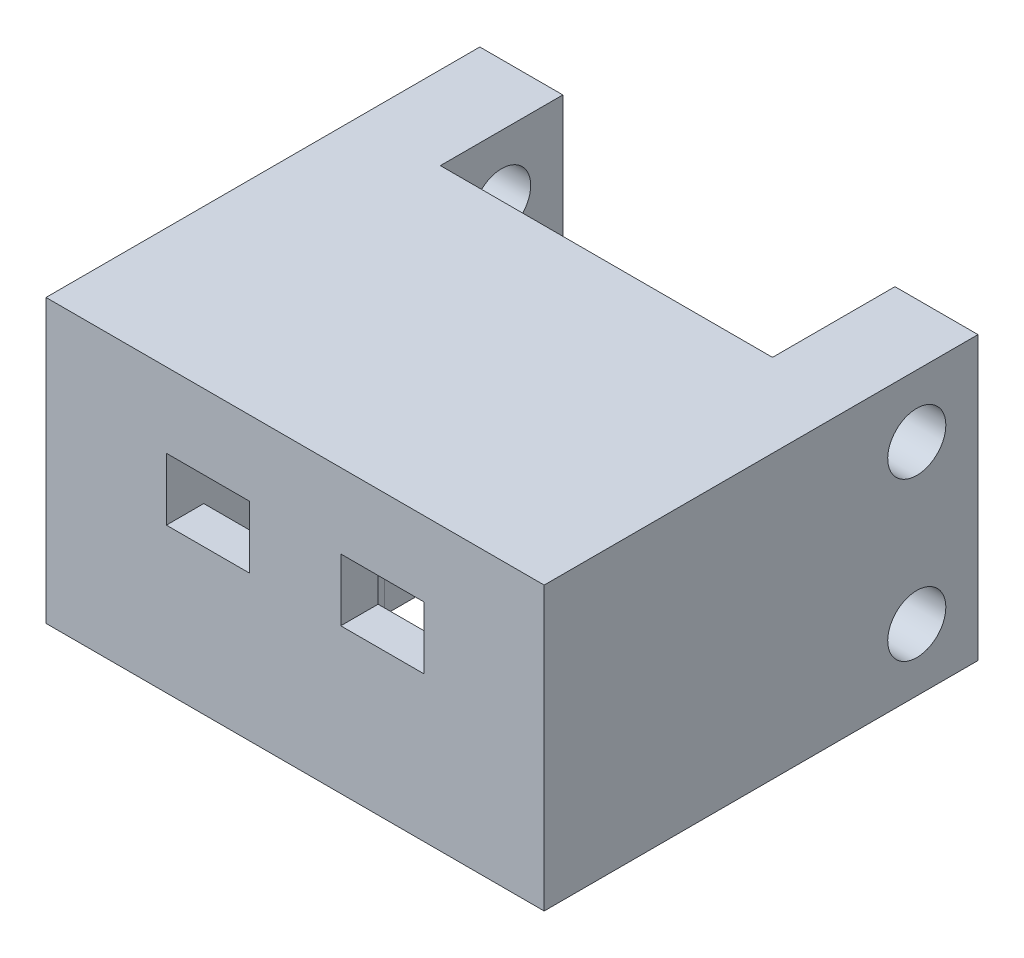
SolidWorks part; units mm, degrees
ref_plane "前视基准面" through (0, 0, 0) normal (0, 0, 1) x (1, 0, 0)
ref_plane "上视基准面" through (0, 0, 0) normal (0, 1, 0) x (1, 0, 0)
ref_plane "右视基准面" through (0, 0, 0) normal (1, 0, 0) x (0, 0, -1)
other "Configuration Table"
sketch "草图1" plane through (0, 0, 0) normal (0, 1, 0) x (1, 0, 0)
  line L0 (-4, 0) -> (4, 0) construction
  line L1 (-4, -4.25) -> (4, -4.25)
  line L2 (-4, -4.25) -> (-4, 3.25)
  line L3 (-4, 3.25) -> (4, 3.25)
  line L4 (4, -4.25) -> (4, 3.25)
  line L6 (-2.1, 0) -> (2.1, 0)
  line L7 (-2.1, 0) -> (-2.1, 3.25)
  line L8 (-2.1, 3.25) -> (2.1, 3.25)
  line L9 (2.1, 0) -> (2.1, 3.25)
  circle A0 centre (0, 0) radius 2.1
  dimension "D3" = 4.2
  dimension "D1" = 7.5
  dimension "D2" = 3.25
  dimension "D4" = 8
extrude "凸台-拉伸1" add sketch "草图1" along normal blind 1 contours L2 L3 L4 L1 | A0 | L9 L8 L7 L6
sketch "草图3" plane through (0, 1, 0) normal (0, 1, 0) x (1, 0, 0)
  line L0 (-4, -4.25) -> (4, -4.25) construction
  line L1 (-4, 3.25) -> (-3.1, 3.25)
  line L2 (-4, 3.25) -> (-4, -4.25)
  line L3 (-4, -4.25) -> (-3.1, -4.25)
  line L4 (-3.1, 3.25) -> (-3.1, -4.25)
  line L5 (-4, 3.25) -> (-2.1, 3.25) construction
  line L6 (4, -4.25) -> (3.1, -4.25)
  line L7 (4, -4.25) -> (4, 3.25)
  line L8 (4, 3.25) -> (3.1, 3.25)
  line L9 (3.1, -4.25) -> (3.1, 3.25)
  line L11 (-4, -4.25) -> (4, -4.25)
  line L12 (-4, -4.25) -> (-4, -3.35)
  line L13 (-4, -3.35) -> (4, -3.35)
  line L14 (4, -4.25) -> (4, -3.35)
  line M11 (-4, -4.25) -> (4, -4.25)
  dimension "D1" = 0.9
  dimension "D2" = 0.9
extrude "凸台-拉伸2" add sketch "草图3" along normal blind 4.8 contours L13 L4 L9 M11
sketch "草图4" plane through (0, 0, 4.25) normal (0, 0, 1) x (1, 0, 0)
  line L0 (-4, 0) -> (4, 0) construction
  line L1 (4, 5.8) -> (6, 5.8)
  line L2 (4, 5.8) -> (4, 0)
  line L3 (4, 0) -> (6, 0)
  line L4 (6, 5.8) -> (6, 0)
  line L5 (-4, 5.8) -> (-6, 5.8)
  line L6 (-4, 5.8) -> (-4, 0)
  line L7 (-4, 0) -> (-6, 0)
  line L8 (-6, 5.8) -> (-6, 0)
  point P10 (0, 0)
  dimension "D1" = 2
extrude "凸台-拉伸3" add sketch "草图4" against normal blind 10.45
sketch "草图5" plane through (0, 5.8, 0) normal (0, 1, 0) x (1, 0, 0)
  line L0 (6, 6.2) -> (6, -4.25) construction
  line L1 (-6, -4.25) -> (6, -4.25)
  line L2 (-6, -4.25) -> (-6, 3.25)
  line L3 (-6, 3.25) -> (6, 3.25)
  line L4 (6, -4.25) -> (6, 3.25)
  line L5 (-4, 6.2) -> (-4, 3.25) construction
  line L6 (-6, 6.2) -> (-4, 6.2)
  line L7 (-6, 6.2) -> (-6, 3.25)
  line L8 (-6, 3.25) -> (-4, 3.25)
  line L9 (-4, 6.2) -> (-4, 3.25)
  line L10 (4, 6.2) -> (6, 6.2)
  line L11 (4, 6.2) -> (4, 3.25)
  line L12 (4, 3.25) -> (6, 3.25)
  line L13 (6, 6.2) -> (6, 3.25)
  point P11 (0, 0)
  point P15 (-3.0275, 3.25)
  line M5 (3.1, -3.35) -> (-3.1, -3.35)
  line M6 (-3.1, -3.35) -> (-3.1, 3.25)
  line M7 (-3.1, 3.25) -> (-4, 3.25)
  line M8 (-4, 3.25) -> (-4, 6.2)
  line M9 (-4, 6.2) -> (-6, 6.2)
  line M10 (-6, 6.2) -> (-6, -4.25)
  line M11 (-6, -4.25) -> (6, -4.25)
  line M12 (6, -4.25) -> (6, 6.2)
  line M13 (6, 6.2) -> (4, 6.2)
  line M14 (4, 6.2) -> (4, 3.25)
  line M15 (4, 3.25) -> (3.1, 3.25)
  line M16 (3.1, 3.25) -> (3.1, -3.35)
  dimension "D1" = 7.5
extrude "凸台-拉伸4" add sketch "草图5" along normal blind 1 contours L3 M10 M11 M12 M15 M16 M5 M6 M7 | L3 M6 M5 M16 | L3 M10 M8 M9 | L3 M14 M12 M13 | L13 L10 L11 L12 | L8 L9 L6 L7 | L2 L1 L4
sketch "草图6" plane through (0, 0, 4.25) normal (0, 0, 1) x (1, 0, 0)
  line L0 (-6, 6.8) -> (-6, 0) construction
  line L1 (-3.1, 5) -> (-1.1, 5)
  line L2 (-3.1, 5) -> (-3.1, 3.5)
  line L3 (-3.1, 3.5) -> (-1.1, 3.5)
  line L4 (-1.1, 5) -> (-1.1, 3.5)
  line L5 (1.1, 5) -> (3.1, 5)
  line L6 (1.1, 5) -> (1.1, 3.5)
  line L7 (1.1, 3.5) -> (3.1, 3.5)
  line L8 (3.1, 5) -> (3.1, 3.5)
  line L9 (6, 0) -> (6, 6.8) construction
  line L10 (-6, 6.8) -> (6, 6.8) construction
  point P10 (-3.1, 4.25)
  dimension "D1" = 2.9
  dimension "D2" = 2.9
  dimension "D3" = 2
  dimension "D4" = 1.8
  dimension "D5" = 1.5
extrude "切除-拉伸1" cut sketch "草图6" against normal through all
sketch "草图7" plane through (-6, 0, 0) normal (-1, 0, 0) x (0, 0, 1)
  line L0 (-6.2, 6.8) -> (-6.2, 0) construction
  line L1 (-6.2, 0) -> (4.25, 0) construction
  line L2 (-6.2, 6.8) -> (4.25, 6.8) construction
  circle A0 centre (-4.725, 5.3) radius 0.7
  circle A1 centre (-4.725, 1.5) radius 0.7
  point P6 (0, 0)
  point P7 (0, 0)
  point P8 (0, 0)
  dimension "D1" = 1.4
  dimension "D2" = 1.475
  dimension "D3" = 1.5
  dimension "D4" = 1.5
extrude "切除-拉伸2" cut sketch "草图7" against normal through all contours A0 | A1
